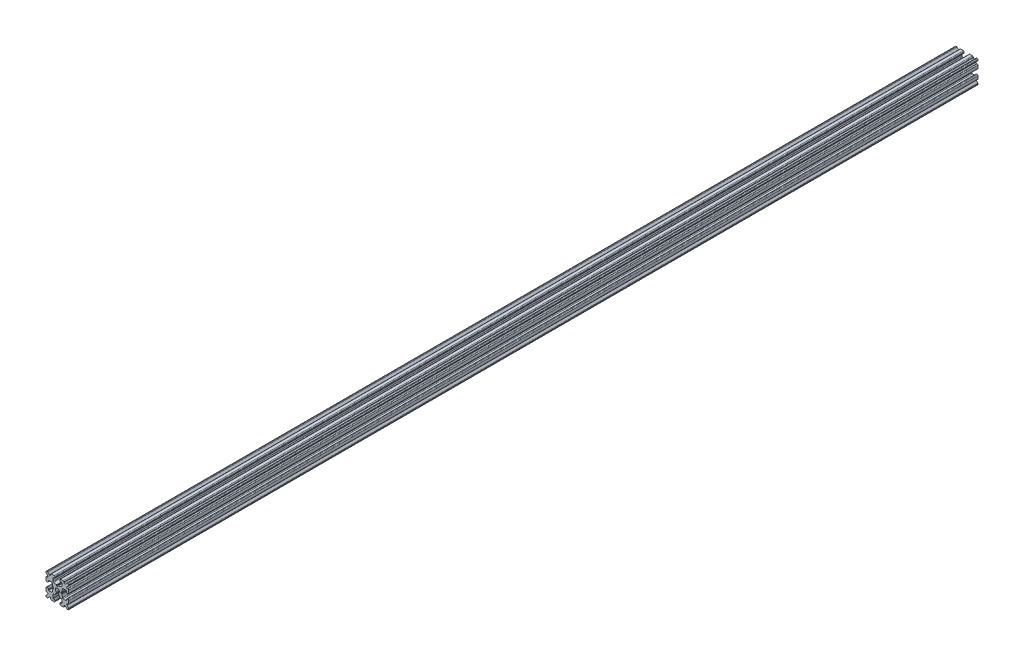
SolidWorks part; units mm, degrees
ref_plane "Front Plane" through (0, 0, 0) normal (0, 0, 1) x (1, 0, 0)
ref_plane "Top Plane" through (0, 0, 0) normal (0, 1, 0) x (1, 0, 0)
ref_plane "Right Plane" through (0, 0, 0) normal (1, 0, 0) x (0, 0, -1)
sketch "Sketch1" plane through (0, 0, 0) normal (0, 0, 1) x (1, 0, 0)
  line L1 (-7.5, -7.5) -> (7.5, -7.5)
  line L2 (-7.5, -7.5) -> (-7.5, 7.5)
  line L3 (-7.5, 7.5) -> (7.5, 7.5)
  line L4 (7.5, -7.5) -> (7.5, 7.5)
  line L5 (-7.5, -7.5) -> (7.5, 7.5) construction
  line L6 (-7.5, 7.5) -> (7.5, -7.5) construction
  circle A0 centre (0, 0) radius 1.35
  point P0 (0, 0)
  dimension "D2" = 2.7
  dimension "D1" = 15
extrude "Boss-Extrude1" add sketch "Sketch1" along normal mid plane 600
fillet "Fillet1" radius 0.5 4 edges at (7.5, -7.5, 0) (-7.5, -7.5, 0) (7.5, 7.5, 0) (-7.5, 7.5, 0)
sketch "Sketch2" plane through (0, 0, 300) normal (0, 0, 1) x (1, 0, 0)
  line L0 (-7.5, 7) -> (-7.5, -7) construction
  line L1 (-7.5, 1.6) -> (-6, 1.6)
  line L2 (-7.5, 1.6) -> (-7.5, -1.6)
  line L3 (-7.5, -1.6) -> (-6, -1.6)
  line L4 (-6, 1.6) -> (-6, 2.9)
  line L5 (0, 0) -> (-12.1036, 0) construction
  line L6 (-6, -2.9) -> (-3.4, -2.9)
  line L7 (0, 0) -> (-7, 7) construction
  line L8 (-6, 2.9) -> (-3.4, 2.9)
  line L9 (-3.4, -2.9) -> (-3.4, 2.9)
  line L10 (55, 0) -> (-55, 0) construction
  line L11 (-6, -2.9) -> (-6, -1.6)
  line L12 (2.9, 6) -> (1.6, 6)
  line L13 (2.9, 3.4) -> (-2.9, 3.4)
  line L14 (-2.9, 6) -> (-2.9, 3.4)
  line L15 (2.9, 6) -> (2.9, 3.4)
  line L16 (-1.6, 6) -> (-2.9, 6)
  line L17 (1.6, 7.5) -> (1.6, 6)
  line L18 (-1.6, 7.5) -> (1.6, 7.5)
  line L19 (-1.6, 7.5) -> (-1.6, 6)
  line L20 (-1.6, -7.5) -> (-1.6, -6)
  line L21 (-1.6, -7.5) -> (1.6, -7.5)
  line L22 (1.6, -7.5) -> (1.6, -6)
  line L23 (-1.6, -6) -> (-2.9, -6)
  line L24 (2.9, -6) -> (2.9, -3.4)
  line L25 (-2.9, -6) -> (-2.9, -3.4)
  line L26 (2.9, -3.4) -> (-2.9, -3.4)
  line L27 (2.9, -6) -> (1.6, -6)
  line L28 (6, -2.9) -> (6, -1.6)
  line L29 (3.4, -2.9) -> (3.4, 2.9)
  line L30 (6, 2.9) -> (3.4, 2.9)
  line L31 (6, -2.9) -> (3.4, -2.9)
  line L32 (6, 1.6) -> (6, 2.9)
  line L33 (7.5, -1.6) -> (6, -1.6)
  line L34 (7.5, 1.6) -> (7.5, -1.6)
  line L35 (7.5, 1.6) -> (6, 1.6)
  dimension "D1" = 3.2
  dimension "D2" = 5.8
  dimension "D3" = 1.5
  dimension "D4" = 2.6
extrude "Cut-Extrude1" cut sketch "Sketch2" against normal through all
sketch "Sketch4" plane through (0, 0, 300) normal (0, 0, 1) x (1, 0, 0)
  line L0 (-3.4, 2.9) -> (-2.85, 0)
  line L1 (55, 0) -> (-55, 0) construction
  line L2 (-2.85, 0) -> (-3.4, -2.9)
  line L3 (-3.4, -2.9) -> (-3.4, 2.9) construction
  line L4 (-3.4, 2.9) -> (-3.4, -2.9)
  line L5 (-2.9, 3.4) -> (0, 2.85)
  line L6 (0, 2.85) -> (2.9, 3.4)
  line L7 (2.9, 3.4) -> (-2.9, 3.4)
  line L8 (3.4, 2.9) -> (2.85, 0)
  line L9 (2.85, 0) -> (3.4, -2.9)
  line L10 (3.4, -2.9) -> (3.4, 2.9)
  line L11 (-2.9, -3.4) -> (0, -2.85)
  line L12 (0, -2.85) -> (2.9, -3.4)
  line L13 (2.9, -3.4) -> (-2.9, -3.4)
  circle A2 centre (0, 0) radius 2.85
  circle A3 centre (0, 0) radius 2.85 construction
  dimension "D1" = 1.5
extrude "Cut-Extrude3" cut sketch "Sketch4" against normal through all
fillet "Fillet3" radius 0.5 16 edges at (-6, -1.6, 0) (-7.5, -1.6, 0) (-6, 1.6, 0) (-7.5, 1.6, 0) (-1.6, -7.5, 0) (-1.6, -6, 0) (1.6, -7.5, 0) (1.6, -6, 0) (6, -1.6, 0) (7.5, -1.6, 0) (7.5, 1.6, 0) (6, 1.6, 0) (1.6, 7.5, 0) (1.6, 6, 0) (-1.6, 7.5, 0) (-1.6, 6, 0)
fillet "Fillet4" radius 0.5 8 edges at (-3.4, 2.9, 0) (-3.4, -2.9, 0) (2.9, -3.4, 0) (-2.9, -3.4, 0) (3.4, -2.9, 0) (3.4, 2.9, 0) (-2.9, 3.4, 0) (2.9, 3.4, 0)
fillet "Fillet5" radius 3 4 edges at (0, -2.85, 0) (2.85, 0, 0) (-2.85, 0, 0) (0, 2.85, 0)
fillet "Fillet6" radius 0.2 8 edges at (-2.9, -6, 0) (2.9, -6, 0) (6, -2.9, 0) (6, 2.9, 0) (2.9, 6, 0) (-2.9, 6, 0) (-6, -2.9, 0) (-6, 2.9, 0)
sketch "Sketch5" plane through (0, 0, 300) normal (0, 0, 1) x (1, 0, 0)
  line L0 (0, 0) -> (-7, 7) construction
  line L1 (-7.5, 6.4393) -> (-5.4607, 4.4)
  line L2 (-6.4393, 7.5) -> (-4.4, 5.4607)
  line L3 (-7.5, 4.4) -> (-5.4607, 4.4)
  line L4 (-3.8141, 2.9) -> (-5.8, 2.9) construction
  line L5 (0, 0) -> (-12.1819, 0) construction
  line L6 (-4.4, 7.5) -> (-4.4, 5.4607)
  line L7 (-2.9, 5.8) -> (-2.9, 3.8141) construction
  line L8 (-7.5, 6.4393) -> (-7.5, 4.4)
  line L9 (-7.5, 7) -> (-7.5, 2.1) construction
  line L10 (2.1, -7.5) -> (7, -7.5) construction
  line L11 (7.5, -7) -> (7.5, -2.1) construction
  line L12 (7, 7.5) -> (2.1, 7.5) construction
  line L13 (-2.1, 7.5) -> (-7, 7.5) construction
  line L14 (-4.4, 7.5) -> (-6.4393, 7.5)
  line L16 (55, 0) -> (-55, 0) construction
  line L17 (0, 0) -> (0, 10.993) construction
  line L18 (0, -54.6431) -> (0, 54.6431) construction
  line L20 (4.4, 7.5) -> (6.4393, 7.5)
  line L22 (7.5, 6.4393) -> (7.5, 4.4)
  line L23 (4.4, 7.5) -> (4.4, 5.4607)
  line L24 (7.5, 4.4) -> (5.4607, 4.4)
  line L25 (6.4393, 7.5) -> (4.4, 5.4607)
  line L26 (7.5, 6.4393) -> (5.4607, 4.4)
  line L27 (7.5, -6.4393) -> (5.4607, -4.4)
  line L28 (6.4393, -7.5) -> (4.4, -5.4607)
  line L29 (7.5, -4.4) -> (5.4607, -4.4)
  line L30 (4.4, -7.5) -> (4.4, -5.4607)
  line L31 (7.5, -6.4393) -> (7.5, -4.4)
  line L33 (4.4, -7.5) -> (6.4393, -7.5)
  line L36 (-4.4, -7.5) -> (-6.4393, -7.5)
  line L38 (-7.5, -6.4393) -> (-7.5, -4.4)
  line L39 (-4.4, -7.5) -> (-4.4, -5.4607)
  line L40 (-7.5, -4.4) -> (-5.4607, -4.4)
  line L41 (-6.4393, -7.5) -> (-4.4, -5.4607)
  line L42 (-7.5, -6.4393) -> (-5.4607, -4.4)
  dimension "D1" = 1.5
  dimension "D2" = 1.5
  dimension "D3" = 1.5
extrude "Cut-Extrude4" cut sketch "Sketch5" against normal through all
fillet "Fillet8" radius 0.5 24 edges at (-5.4607, 4.4, 0) (-7.5, 4.4, 0) (-5.4607, -4.4, 0) (-7.5, -4.4, 0) (-4.4, -7.5, 0) (-4.4, -5.4607, 0) (4.4, -7.5, 0) (4.4, -5.4607, 0) (5.4607, -4.4, 0) (7.5, -4.4, 0) (7.5, 4.4, 0) (5.4607, 4.4, 0) (4.4, 5.4607, 0) (4.4, 7.5, 0) (-4.4, 5.4607, 0) (-4.4, 7.5, 0) (-6.4393, 7.5, 0) (-7.5, 6.4393, 0) (6.4393, 7.5, 0) (7.5, 6.4393, 0) (6.4393, -7.5, 0) (7.5, -6.4393, 0) (-6.4393, -7.5, 0) (-7.5, -6.4393, 0)
sketch "Sketch6" plane through (0, 0, 300) normal (0, 0, 1) x (1, 0, 0)
  line L0 (0, 0) -> (0, 11.013) construction
  line L1 (0.559, 2.956) -> (2.1235, 2.956) construction
  line L2 (0, -54.6431) -> (0, 54.6431) construction
  line L3 (0, 0) -> (7, 7) construction
  line L4 (8.6552, 0.4445) -> (8.6552, -0.4445)
  line L5 (2.406, 0.4445) -> (8.6552, 0.4445)
  line L8 (2.406, -0.4445) -> (2.406, 0.4445)
  line L10 (8.6552, -0.4445) -> (2.406, -0.4445)
  line L11 (-8.6552, -0.4445) -> (-2.406, -0.4445)
  line L12 (-2.406, -0.4445) -> (-2.406, 0.4445)
  line L14 (-0.4445, 8.6552) -> (-0.4445, 2.406)
  line L15 (-0.4445, 2.406) -> (0.4445, 2.406)
  line L17 (0.4445, 2.406) -> (0.4445, 8.6552)
  line L18 (0.4445, 8.6552) -> (-0.4445, 8.6552)
  line L20 (-2.406, 0.4445) -> (-8.6552, 0.4445)
  line L21 (-8.6552, 0.4445) -> (-8.6552, -0.4445)
  point P7 (0, 2.5973)
  dimension "D3" = 0.55
  dimension "D1" = 0.889
extrude "Cut-Extrude5" cut sketch "Sketch6" against normal through all
sketch "Sketch7" plane through (0, 0, 300) normal (0, 0, 1) x (1, 0, 0)
  line L0 (0, 0) -> (-2.1533, -4.6178)
  line L1 (-2.1533, -4.6178) -> (2.1533, -4.6178)
  line L2 (2.1533, -4.6178) -> (0, 0)
  line L3 (0, 0) -> (0, -8.6832) construction
  line L4 (0, -54.6431) -> (0, 54.6431) construction
  dimension "D1" = 50
extrude "Cut-Extrude6" cut sketch "Sketch7" against normal through all
fillet "Fillet9" radius 0.5 4 edges at (0.5705, -1.2235, 0) (-0.5705, -1.2235, 0) (1.4579, -3.1265, 0) (-1.4579, -3.1265, 0)
fillet "Fillet10" radius 0.2 12 edges at (-2.406, 0.4445, 0) (-2.406, -0.4445, 0) (0.4445, 2.406, 0) (-0.4445, 2.406, 0) (2.406, 0.4445, 0) (2.406, -0.4445, 0) (-2.9366, -0.4445, 0) (-2.9366, 0.4445, 0) (2.9366, -0.4445, 0) (2.9366, 0.4445, 0) (0.4445, 2.9366, 0) (-0.4445, 2.9366, 0)
sketch "Sketch10" plane through (0, 0, 300) normal (0, 0, 1) x (1, 0, 0)
  line L0 (2.7, 6) -> (2.1, 6) construction
  line L1 (-2.75, 6) -> (2.75, 6)
  line L2 (-2.75, 6) -> (-2.75, 3.6)
  line L3 (-2.75, 3.6) -> (2.75, 3.6)
  line L4 (2.75, 6) -> (2.75, 3.6)
  line L5 (0, 0) -> (0, 8.8277) construction
  line L6 (-3.2398, 3.994) -> (-2.2083, 2.8606) construction
  line L7 (-3.878, 3.2131) -> (-3.2018, 2.4701) construction
  line L8 (-2.406, -0.2445) -> (-2.406, 0.2445) construction
  line L9 (-2.1, 7.5) -> (-3.9, 7.5) construction
  line L10 (-1.5, 7.5) -> (1.5, 7.5)
  line L11 (-1.5, 7.5) -> (-1.5, 3.5)
  line L12 (-1.5, 3.5) -> (1.5, 3.5)
  line L13 (1.5, 7.5) -> (1.5, 3.5)
  arc A1 (-3.3228, 2.4932) -> (-3.8141, 2.9) centre (-3.8141, 2.4) ccw construction
  arc A2 (-2.9, 3.8141) -> (-2.4932, 3.3228) centre (-2.4, 3.8141) ccw construction
  arc A3 (0.88, -1.0238) -> (-0.88, -1.0238) centre (0, 0) ccw construction
  point P19 (-1.35, 0)
  point P20 (-2.406, 0)
  dimension "D1" = 2.4
  dimension "D2" = 5.5
  dimension "D3" = 0.9976
  dimension "D4" = 3
  dimension "D5" = 4
sketch "Sketch11" plane through (0, 0, 300) normal (0, 0, 1) x (1, 0, 0)
  line L0 (-7.5, 7) -> (-7.5, 6.6464) construction
  line L1 (-7.5, 7.5) -> (7.5, 7.5) construction
  line L2 (-7.5, 7.5) -> (-7.5, -7.5) construction
  line L3 (-7.5, -7.5) -> (7.5, -7.5) construction
  line L4 (7.5, 7.5) -> (7.5, -7.5) construction
  line L5 (-7, -7.5) -> (-6.6464, -7.5) construction
  line L6 (7.5, 6.6464) -> (7.5, 7) construction
  line L7 (-2.1, 7.5) -> (-3.9, 7.5) construction
  point P0 (0, 7.5)
  point P1 (0, -7.5)
  point P2 (7.5, 0)
  point P3 (-7.5, 0)
sketch "Sketch12" plane through (0, 0, -300) normal (0, 0, -1) x (-1, 0, 0)
  line L1 (-7.5, -7.5) -> (7.5, -7.5) construction
  line L2 (-7.5, -7.5) -> (-7.5, 7.5) construction
  line L3 (-7.5, 7.5) -> (7.5, 7.5) construction
  line L4 (7.5, -7.5) -> (7.5, 7.5) construction
  point P4 (-7.5, 0)
  point P9 (0, -7.5)
  point P10 (7.5, 0)
  point P11 (0, 7.5)
sketch "Sketch13" plane through (0, -7.5, 0) normal (0, -1, 0) x (1, 0, 0)
  line L0 (0, 300) -> (0, -300) construction
  line L1 (-7.5, -300) -> (-7.5, 300) construction
  line L2 (7.5, 300) -> (7.5, -300) construction
sketch "Sketch14" plane through (-7.5, 0, 0) normal (-1, 0, 0) x (0, 0, 1)
  line L0 (300, 0) -> (-300, 0) construction
sketch "Sketch15" plane through (0, 7.5, 0) normal (0, 1, 0) x (1, 0, 0)
  line L0 (0, -300) -> (0, 300) construction
  line L1 (-7.5, -300) -> (7.5, -300) construction
  line L2 (-7.5, -300) -> (-7.5, 300) construction
  line L3 (7.5, 300) -> (7.5, -300) construction
sketch "Sketch16" plane through (7.5, 0, 0) normal (1, 0, 0) x (0, 0, -1)
  line L0 (-300, 0) -> (300, 0) construction
